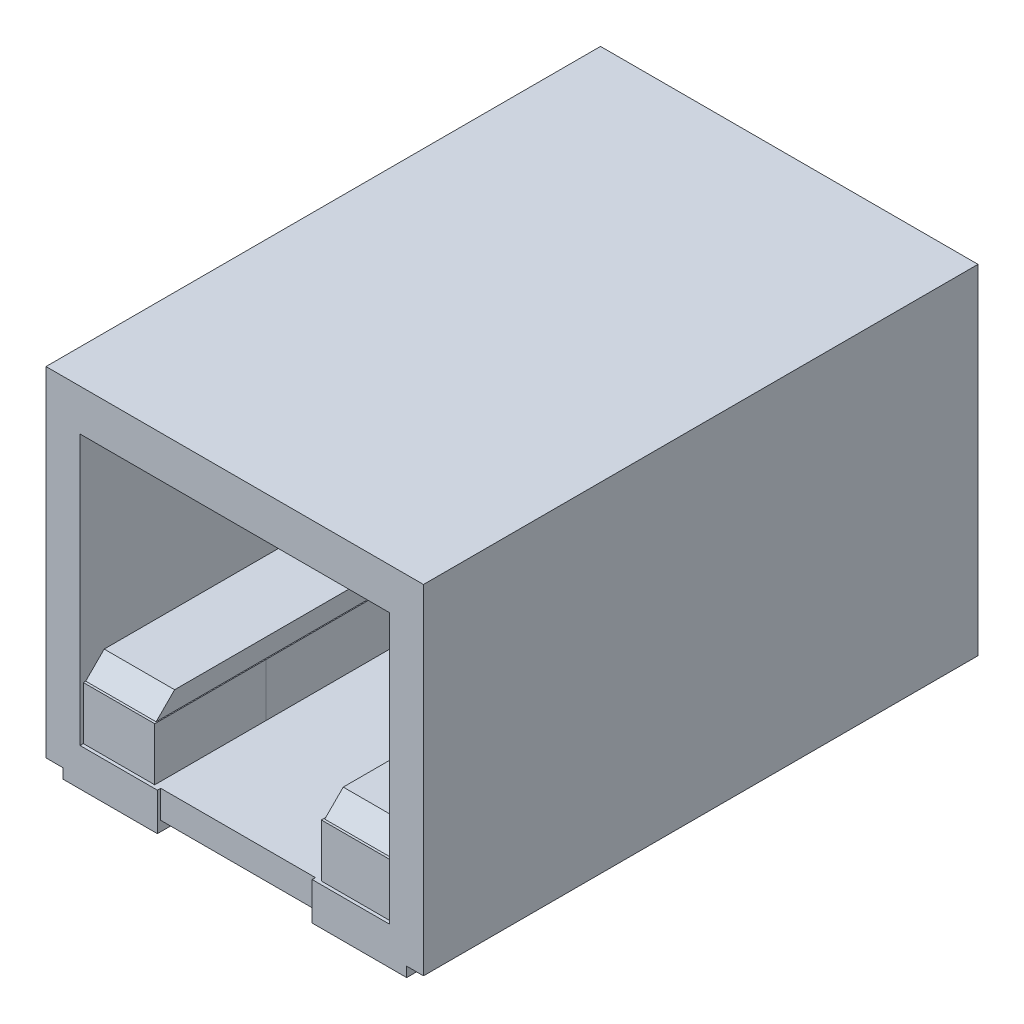
SolidWorks part; units mm, degrees
ref_plane "Front" through (0, 0, 0) normal (0, 0, 1) x (1, 0, 0)
ref_plane "Top" through (0, 0, 0) normal (0, 1, 0) x (1, 0, 0)
ref_plane "Right" through (0, 0, 0) normal (1, 0, 0) x (0, 0, -1)
sketch "Sketch1" plane through (0, 0, 0) normal (1, 0, 0) x (0, 0, -1)
  line L1 (0, 0) -> (-21.3, 0)
  line L2 (0, 0) -> (0, 13.02)
  line L3 (0, 13.02) -> (-21.3, 13.02)
  line L4 (-21.3, 0) -> (-21.3, 13.02)
  dimension "D1" = 21.3
  dimension "D2" = 13.02
extrude "Extrude1" add sketch "Sketch1" along normal mid plane 14.5
sketch "Sketch2" plane through (0, 0, 21.3) normal (0, 0, 1) x (1, 0, 0)
  line L0 (7.25, 0) -> (-7.25, 0) construction
  line L1 (-5.9436, 11.43) -> (5.9436, 11.43)
  line L2 (-5.9436, 11.43) -> (-5.9436, 1.0668)
  line L3 (-5.9436, 1.0668) -> (-2.9718, 1.0668)
  line L4 (5.9436, 11.43) -> (5.9436, 1.0668)
  line L5 (2.9718, 1.0668) -> (5.9436, 1.0668)
  line L7 (-2.9718, 1.0668) -> (-2.9718, 0)
  line L8 (-2.9718, 0) -> (2.9718, 0)
  line L9 (2.9718, 1.0668) -> (2.9718, 0)
  dimension "D1" = 11.8872
  dimension "D2" = 10.3632
  dimension "D3" = 1.0668
  dimension "D4" = 5.9436
  dimension "D5" = 5.9436
  dimension "D6" = 2.9718
extrude "Cut-Extrude1" cut sketch "Sketch2" against normal blind 0.127
sketch "Sketch3" plane through (0, 0, 21.173) normal (0, 0, 1) x (1, 0, 0)
  line L0 (-5.9436, 3.0988) -> (-3.2004, 3.0988)
  line L1 (-3.2004, 3.0988) -> (-3.2004, 1.0668)
  line L2 (3.2004, 1.0668) -> (3.2004, 3.0988)
  line L3 (3.2004, 3.0988) -> (5.9436, 3.0988)
  line L4 (-5.9436, 11.43) -> (-5.9436, 1.0668)
  line L5 (-5.9436, 1.0668) -> (-2.9718, 1.0668)
  line L6 (5.9436, 1.0668) -> (5.9436, 11.43)
  line L7 (5.9436, 11.43) -> (-5.9436, 11.43)
  line L8 (-5.9436, 11.43) -> (-5.9436, 3.0988)
  line L9 (-3.2004, 1.0668) -> (3.2004, 1.0668)
  line L10 (5.9436, 3.0988) -> (5.9436, 11.43)
  line L11 (5.9436, 11.43) -> (-5.9436, 11.43)
  line L20 (-2.9718, 1.0668) -> (-2.9718, 0)
  line L22 (-2.9718, 0) -> (2.9718, 0)
  line L24 (2.9718, 0) -> (2.9718, 1.0668)
  line L26 (2.9718, 1.0668) -> (5.9436, 1.0668)
  dimension "D3" = 6.4008
  dimension "D4" = 3.2004
  dimension "D1" = 0
extrude "Cut-Extrude2" cut sketch "Sketch3" against normal blind 11.303
sketch "Sketch4" plane through (0, 0, 0) normal (1, 0, 0) x (0, 0, -1)
  line L0 (-9.87, 11.43) -> (-21.3, 11.43) construction
  line L1 (-17.5928, 11.43) -> (-18.76, 11.43)
  line L2 (-9.87, 3.0988) -> (-9.87, 11.43) construction
  line L3 (-9.87, 8.128) -> (-9.87, 8.5615)
  line L4 (-18.76, 11.43) -> (-9.87, 8.128)
  line L5 (-17.5928, 11.43) -> (-9.87, 8.5615)
  dimension "D1" = 3.302
  dimension "D2" = 2.54
  dimension "D3" = 0.4064
extrude "Extrude2" add sketch "Sketch4" along normal mid plane 7.5997
sketch "Sketch5" plane through (0, 0, 21.3) normal (0, 0, 1) x (1, 0, 0)
  line L0 (5.9436, 11.43) -> (-5.9436, 11.43) construction
  line L1 (-3.3528, 11.43) -> (-2.9058, 11.43)
  line L2 (-3.3528, 11.43) -> (-3.3528, 8.128)
  line L3 (-3.3528, 8.128) -> (-2.9058, 8.128)
  line L4 (-2.9058, 11.43) -> (-2.9058, 8.128)
  line L5 (3.7998, 8.128) -> (-3.7998, 8.128) construction
  line L6 (-3.7998, 11.43) -> (-3.7998, 8.128) construction
  line L8 (-2.4587, 11.43) -> (-2.0117, 11.43)
  line L9 (-2.4587, 11.43) -> (-2.4587, 8.128)
  line L10 (-2.4587, 8.128) -> (-2.0117, 8.128)
  line L11 (-2.0117, 11.43) -> (-2.0117, 8.128)
  line L12 (-1.5646, 11.43) -> (-1.1176, 11.43)
  line L13 (-1.5646, 11.43) -> (-1.5646, 8.128)
  line L14 (-1.5646, 8.128) -> (-1.1176, 8.128)
  line L15 (-1.1176, 11.43) -> (-1.1176, 8.128)
  line L16 (-0.6706, 11.43) -> (-0.2235, 11.43)
  line L17 (-0.6706, 11.43) -> (-0.6706, 8.128)
  line L18 (-0.6706, 8.128) -> (-0.2235, 8.128)
  line L19 (-0.2235, 11.43) -> (-0.2235, 8.128)
  line L20 (0.2235, 11.43) -> (0.6706, 11.43)
  line L21 (0.2235, 11.43) -> (0.2235, 8.128)
  line L22 (0.2235, 8.128) -> (0.6706, 8.128)
  line L23 (0.6706, 11.43) -> (0.6706, 8.128)
  line L24 (1.1176, 11.43) -> (1.5646, 11.43)
  line L25 (1.1176, 11.43) -> (1.1176, 8.128)
  line L26 (1.1176, 8.128) -> (1.5646, 8.128)
  line L27 (1.5646, 11.43) -> (1.5646, 8.128)
  line L28 (2.0117, 11.43) -> (2.4587, 11.43)
  line L29 (2.0117, 11.43) -> (2.0117, 8.128)
  line L30 (2.0117, 8.128) -> (2.4587, 8.128)
  line L31 (2.4587, 11.43) -> (2.4587, 8.128)
  line L32 (2.9058, 11.43) -> (3.3528, 11.43)
  line L33 (2.9058, 11.43) -> (2.9058, 8.128)
  line L34 (2.9058, 8.128) -> (3.3528, 8.128)
  line L35 (3.3528, 11.43) -> (3.3528, 8.128)
  dimension "D1" = 0.447
  dimension "D2" = 0.447
  dimension "D3" = 0.447
  dimension "D4" = 0.447
  dimension "D5" = 0.447
  dimension "D6" = 0.447
  dimension "D7" = 0.447
  dimension "D8" = 0.447
  dimension "D9" = 0.447
  dimension "D10" = 0.447
  dimension "D11" = 0.447
  dimension "D12" = 0.447
  dimension "D13" = 0.447
  dimension "D14" = 0.447
  dimension "D15" = 0.447
  dimension "D16" = 0.447
extrude "Cut-Extrude3" cut sketch "Sketch5" against normal up to surface (11.43 mm away)
sketch "Sketch6" plane through (-5.9436, 0, 0) normal (1, 0, 0) x (0, 0, -1)
  line L0 (-9.87, 3.0988) -> (-21.173, 3.0988) construction
  line L1 (-9.87, 3.0988) -> (-21.082, 3.0988)
  line L2 (-21.082, 3.0988) -> (-20.3708, 3.81)
  line L3 (-20.3708, 3.81) -> (-12.446, 3.81)
  line L4 (-12.446, 3.81) -> (-12.446, 4.826)
  line L5 (-12.446, 4.826) -> (-9.87, 4.826)
  line L6 (-9.87, 3.0988) -> (-9.87, 11.43) construction
  line L7 (-9.87, 4.826) -> (-9.87, 3.0988)
  line L9 (-21.3, 0) -> (0, 0) construction
  dimension "D1" = 3.81
  dimension "D2" = 12.446
  dimension "D3" = 4.826
  dimension "D4" = 21.082
  dimension "D5" = 45
extrude "Extrude3" add sketch "Sketch6" along normal blind 2.7051
mirror "Mirror1" about plane through (0, 0, 0) normal (1, 0, 0) of "Extrude3"
sketch "Sketch8" plane through (-3.2004, 0, 0) normal (1, 0, 0) x (0, 0, -1)
  line L0 (-16.891, 3.0988) -> (-16.891, 1.0668)
  line L1 (-21.082, 3.0988) -> (-9.87, 3.0988) construction
  line L2 (-9.87, 1.0668) -> (-21.173, 1.0668) construction
  dimension "D1" = 16.891
split line "Split Line2"
sketch "Sketch9" plane through (3.2004, 0, 0) normal (-1, 0, 0) x (0, 0, 1)
  line L0 (16.891, 3.0988) -> (16.891, 1.0668) construction
  line L1 (16.891, 3.0988) -> (16.891, 1.0668)
split line "Split Line3"
sketch "Sketch11" plane through (0, 3.0988, 0) normal (0, 1, 0) x (-1, 0, 0)
  line L0 (3.2385, 16.891) -> (3.2004, 16.891)
  line L1 (3.2385, 12.446) -> (3.2385, 20.3708) construction
  line L2 (3.2004, 16.891) -> (3.2004, 21.173) construction
  dimension "D1" = 16.891
split line "Split Line4"
sketch "Sketch12" plane through (0, 3.0988, 0) normal (0, 1, 0) x (-1, 0, 0)
  line L0 (-3.2385, 16.891) -> (-3.2004, 16.891)
  line L1 (-3.2385, 12.446) -> (-3.2385, 20.3708) construction
  line L2 (-3.2004, 16.891) -> (-3.2004, 21.173) construction
  dimension "D1" = 16.891
split line "Split Line5"
sketch "Sketch14" plane through (0, 0, 0) normal (0, -1, 0) x (1, 0, 0)
  line L1 (-6.604, 21.3) -> (-2.9718, 21.3)
  line L3 (-6.604, 18.252) -> (6.604, 18.252)
  line L5 (-2.9718, 21.173) -> (-2.9718, 21.3) construction
  line L6 (-6.604, 21.3) -> (-6.604, 18.252)
  line L7 (2.9718, 21.3) -> (2.9718, 20.792)
  line L8 (2.9718, 20.792) -> (-2.9718, 20.792)
  line L9 (-2.9718, 21.3) -> (-2.9718, 20.792)
  line L10 (2.9718, 21.3) -> (6.604, 21.3)
  line L11 (6.604, 21.3) -> (6.604, 18.252)
  dimension "D1" = 0.508
  dimension "D2" = 3.048
  dimension "D3" = 13.208
  dimension "D4" = 6.604
extrude "Extrude4" add sketch "Sketch14" along normal blind 0.381
sketch "Sketch15" plane through (0, 0, 0) normal (0, -1, 0) x (1, 0, 0)
  line L0 (6.927, 21.3) -> (6.927, 0)
  line L1 (7.25, 21.3) -> (6.604, 21.3) construction
  line L2 (7.25, 0) -> (-7.25, 0) construction
split line "Split Line7"
sketch "Sketch16" plane through (0, 0, 0) normal (0, -1, 0) x (1, 0, 0)
  line L0 (-6.927, 21.3) -> (-6.927, 0)
  line L1 (-6.604, 21.3) -> (-7.25, 21.3) construction
  line L2 (6.927, 0) -> (-7.25, 0) construction
split line "Split Line8"
